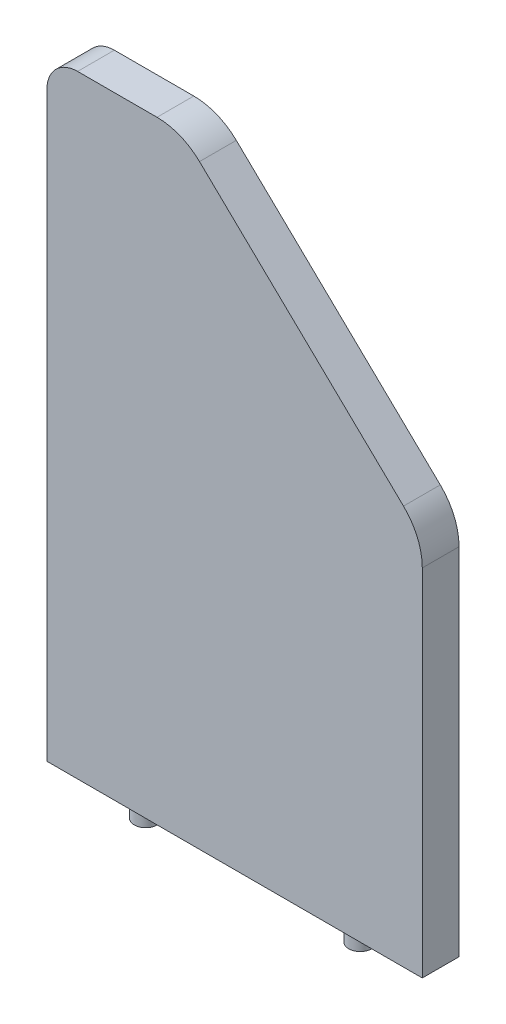
SolidWorks part; units mm, degrees
ref_plane "Front Plane" through (0, 0, 0) normal (0, 0, 1) x (1, 0, 0)
ref_plane "Top Plane" through (0, 0, 0) normal (0, 1, 0) x (1, 0, 0)
ref_plane "Right Plane" through (0, 0, 0) normal (1, 0, 0) x (0, 0, -1)
sketch "Sketch4" plane through (0, 0, 0) normal (0, 0, 1) x (1, 0, 0)
  line L1 (0, 0) -> (122.5, 0)
  line L2 (0, 0) -> (0, 200)
  line L3 (0, 200) -> (122.5, 200)
  line L4 (122.5, 0) -> (122.5, 200)
  dimension "D1" = 122.5
  dimension "D2" = 200
extrude "Boss-Extrude1" add sketch "Sketch4" along normal blind 12
sketch "Sketch7" plane through (0, 0, 12) normal (0, 0, 1) x (1, 0, 0)
  line L1 (122.5, 200) -> (0, 200) construction
  line L2 (43.9858, 200) -> (122.5, 124.4158)
  line L3 (122.5, 0) -> (122.5, 200) construction
  line L4 (43.9858, 200) -> (122.5, 200)
  line L5 (122.5, 200) -> (122.5, 124.4158)
extrude "Cut-Extrude1" cut sketch "Sketch7" against normal blind 12
fillet "Fillet1" radius 20 1 edges at (43.9858, 200, 6)
fillet "Fillet2" radius 20 1 edges at (122.5, 124.4158, 6)
fillet "Fillet3" radius 10 1 edges at (0, 200, 6)
sketch "Sketch10" plane through (0, 0, 0) normal (0, -1, 0) x (1, 0, 0)
  circle A0 centre (26.25, 6) radius 3.75
  circle A1 centre (96.25, 6) radius 3.75
extrude "Boss-Extrude3" add sketch "Sketch10" along normal blind 6
sketch "Sketch11" plane through (0, -6, 0) normal (0, -1, 0) x (1, 0, 0)
  circle A0 centre (26.25, 6) radius 3.75
  circle A1 centre (96.25, 6) radius 3.75
extrude "Boss-Extrude4" add sketch "Sketch11" along normal blind 2 draft 62
sketch "Sketch12" plane through (0, 0, 0) normal (-1, 0, 0) x (0, 0, 1)
  line L0 (12, 0) -> (12, 10)
  line L1 (0, 190) -> (0, 0) construction
  line L2 (0, 180) -> (12, 180)
  line L3 (12, 190) -> (12, 0) construction
  line L4 (6, 190) -> (6, 180)
  line L5 (12, 190) -> (0, 190) construction
  line L6 (12, 10) -> (6, 10)
  line L7 (6, 10) -> (6, 0)
  line L8 (12, 0) -> (0, 0) construction
hole_wizard "Ø5.0 (5) Diameter Hole1" positions "Sketch14" profile "Sketch13" hole size "Ø5.0" standard "ANSI Metric"
sketch "Sketch14" plane through (0, 0, 0) normal (-1, 0, 0) x (0, 0, 1)
  point P0 (6, 180)
sketch "Sketch13" plane through (0, 180, 6) normal (0, 1, 0) x (0, 0, 1)
  line L0 (0, 0) -> (0, 9.5022)
  line L1 (0, 9.5022) -> (2.5, 8)
  line L2 (2.5, 8) -> (2.5, 0)
  line L5 (2.5, 0) -> (0, 0)
  line L10 (0, 9.5022) -> (-2.5, 8) construction
  line L11 (0, -6.35) -> (0, 107.95) construction
  dimension "Hole Dia." = 5
  dimension "Hole Depth" = 8
  dimension "Drill Angle" = 118
hole_wizard "Ø5.0 (5) Diameter Hole2" positions "Sketch17" profile "Sketch16" hole size "Ø5.0" standard "ANSI Metric"
sketch "Sketch17" plane through (0, 0, 0) normal (-1, 0, 0) x (0, 0, 1)
  point P0 (6, 10)
sketch "Sketch16" plane through (0, 10, 6) normal (0, 1, 0) x (0, 0, 1)
  line L0 (0, 0) -> (0, 9.5022)
  line L1 (0, 9.5022) -> (2.5, 8)
  line L2 (2.5, 8) -> (2.5, 0)
  line L5 (2.5, 0) -> (0, 0)
  line L10 (0, 9.5022) -> (-2.5, 8) construction
  line L11 (0, -6.35) -> (0, 107.95) construction
  dimension "Hole Dia." = 5
  dimension "Hole Depth" = 8
  dimension "Drill Angle" = 118
scale "Scale1" scale about centroid uniform scaling yes scale factor 0.9
